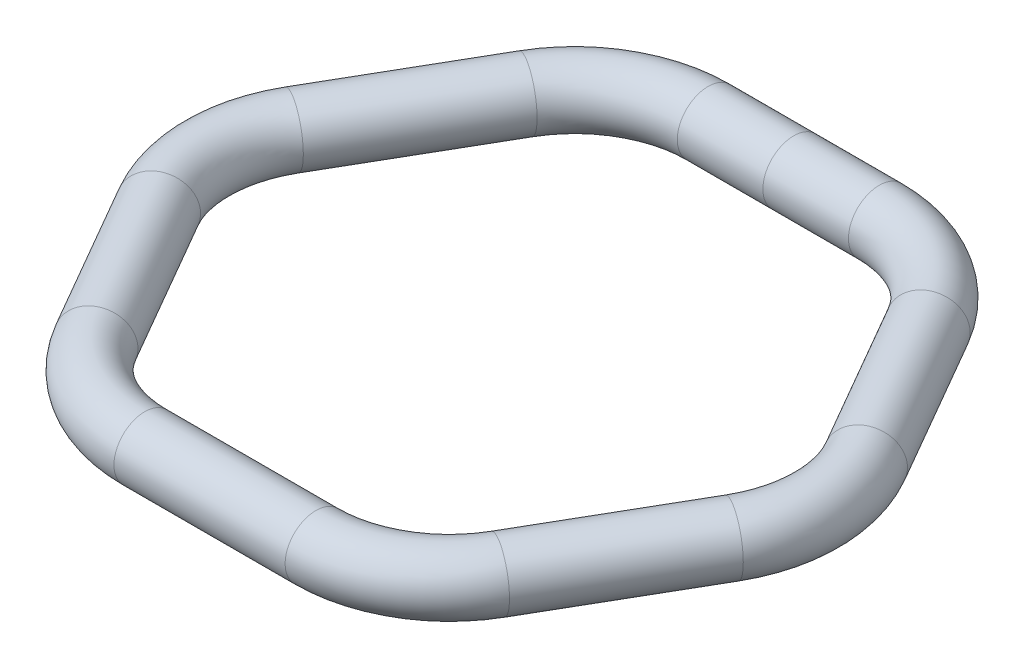
SolidWorks part; units mm, degrees
ref_plane "Front Plane" through (0, 0, 0) normal (0, 0, 1) x (1, 0, 0)
ref_plane "Top Plane" through (0, 0, 0) normal (0, 1, 0) x (1, 0, 0)
ref_plane "Right Plane" through (0, 0, 0) normal (1, 0, 0) x (0, 0, -1)
sketch "Sketch1" plane through (0, 0, 0) normal (0, 1, 0) x (1, 0, 0)
  line L1 (63.3353, 12.5) -> (42.493, 48.6)
  line L2 (20.8423, 61.1) -> (-20.8423, 61.1)
  line L3 (-42.493, 48.6) -> (-63.3353, 12.5)
  line L4 (-63.3353, -12.5) -> (-42.493, -48.6)
  line L5 (-20.8423, -61.1) -> (20.8423, -61.1)
  line L6 (42.493, -48.6) -> (63.3353, -12.5)
  circle A0 centre (0, 0) radius 61.1 construction
  arc A1 (-42.493, -48.6) -> (-20.8423, -61.1) centre (-20.8423, -36.1) ccw
  arc A2 (20.8423, -61.1) -> (42.493, -48.6) centre (20.8423, -36.1) ccw
  arc A3 (63.3353, -12.5) -> (63.3353, 12.5) centre (41.6847, 0) ccw
  arc A4 (42.493, 48.6) -> (20.8423, 61.1) centre (20.8423, 36.1) ccw
  arc A5 (-20.8423, 61.1) -> (-42.493, 48.6) centre (-20.8423, 36.1) ccw
  arc A6 (-63.3353, 12.5) -> (-63.3353, -12.5) centre (-41.6847, 0) ccw
  dimension "D2" = 25
  dimension "D1" = 122.2
sketch "Sketch2" plane through (0, 0, 0) normal (1, 0, 0) x (0, 0, -1)
  circle A4 centre (68.6, 0) radius 7.5
  point P2 (61.1, 0)
  dimension "D1" = 15
sweep "Sweep1" add profiles "Sketch2" path "Sketch1"
